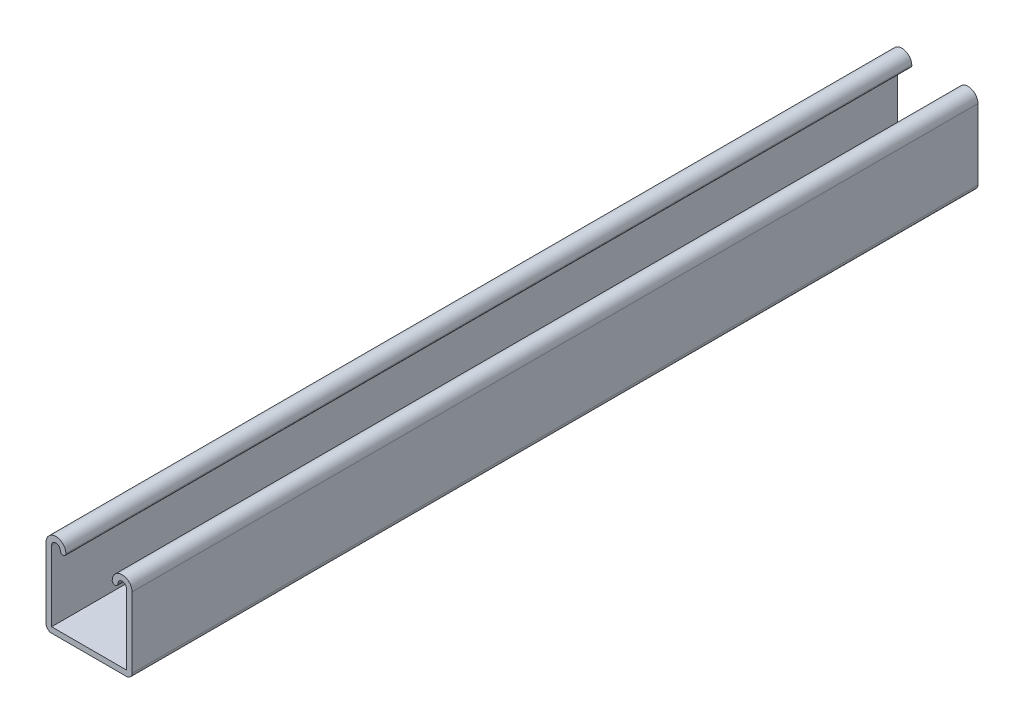
SolidWorks part; units mm, degrees
material "普通碳钢"
ref_plane "前视基准面" through (0, 0, 0) normal (0, 0, 1) x (1, 0, 0)
ref_plane "上视基准面" through (0, 0, 0) normal (0, 1, 0) x (1, 0, 0)
ref_plane "右视基准面" through (0, 0, 0) normal (1, 0, 0) x (0, 0, -1)
sketch "草图1" plane through (0, 0, 0) normal (0, 0, 1) x (1, 0, 0)
  line L0 (0, 0) -> (35.98, 0)
  line L1 (17.99, 2.6924) -> (17.99, -3.3917) construction
  line L2 (35.98, 2.6924) -> (0, 2.6924)
  line L3 (35.98, 19.6088) -> (0, 19.6088) construction
  line L4 (35.98, 2.6924) -> (35.98, 36.5252)
  line L5 (38.6724, 2.6924) -> (38.6724, 36.5252)
  line L6 (-2.6924, 2.6924) -> (-2.6924, 36.5252)
  line L7 (0, 2.6924) -> (0, 36.5252)
  line L8 (17.99, 19.6088) -> (17.99, 2.6924) construction
  arc A0 (35.98, 0) -> (38.6724, 2.6924) centre (35.98, 2.6924) ccw
  arc A1 (35.98, 36.5252) -> (31.8144, 36.5252) centre (33.8972, 36.5252) ccw
  arc A2 (38.6724, 36.5252) -> (29.122, 36.5252) centre (33.8972, 36.5252) ccw
  arc A3 (29.122, 36.5252) -> (31.8144, 36.5252) centre (30.4682, 36.5252) ccw
  arc A4 (6.858, 36.5252) -> (4.1656, 36.5252) centre (5.5118, 36.5252) cw
  arc A5 (-2.6924, 36.5252) -> (6.858, 36.5252) centre (2.0828, 36.5252) cw
  arc A6 (0, 36.5252) -> (4.1656, 36.5252) centre (2.0828, 36.5252) cw
  arc A7 (0, 0) -> (-2.6924, 2.6924) centre (0, 2.6924) cw
  point P25 (17.99, 19.6088)
extrude "凸台-拉伸1" add sketch "草图1" along normal blind 406.4
ref_plane "基准面1" through (0, 0, 0) normal (0, -1, 0) x (-1, 0, 0)
sketch "草图2" plane through (0, 0, 0) normal (0, -1, 0) x (-1, 0, 0)
  line L0 (-35.98, -203.2) -> (0, -203.2) construction
  line L1 (-35.98, -406.4) -> (-35.98, 0) construction
  line L2 (-17.99, -203.2) -> (-17.99, -120.65) construction
  circle A0 centre (-17.99, -120.65) radius 7.112
  circle A1 centre (-17.99, -285.75) radius 7.112
  dimension "D1" = 82.55
extrude "切除-拉伸1" cut sketch "草图2" against normal through all
